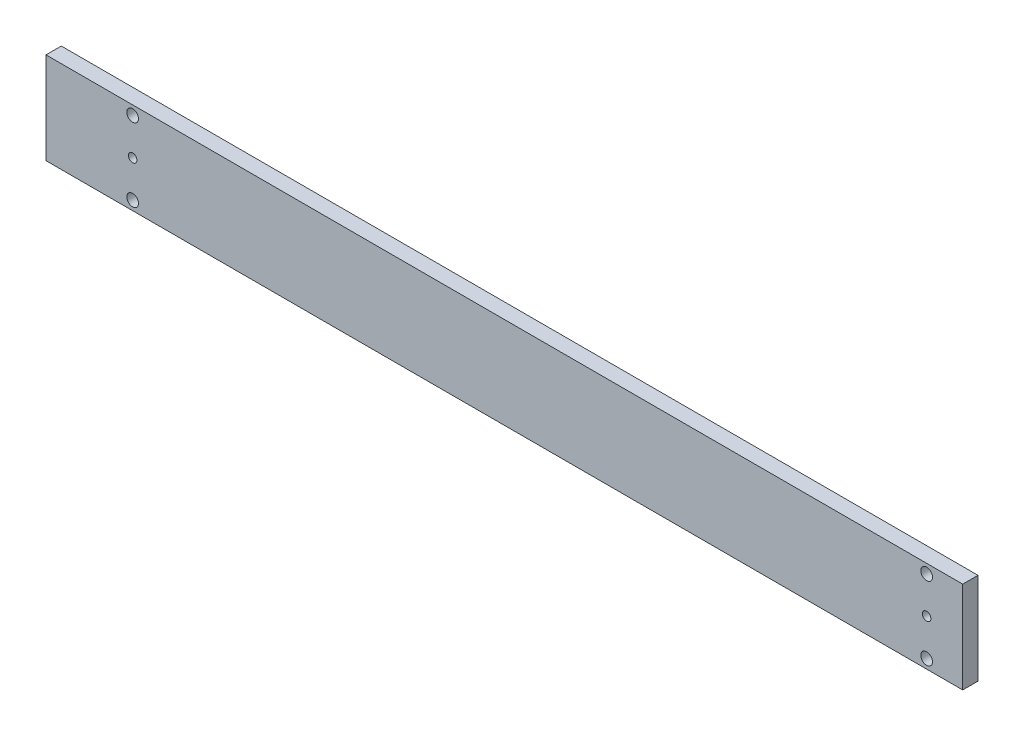
SolidWorks part; units mm, degrees
ref_plane "Front Plane" through (0, 0, 0) normal (0, 0, 1) x (1, 0, 0)
ref_plane "Top Plane" through (0, 0, 0) normal (0, 1, 0) x (1, 0, 0)
ref_plane "Right Plane" through (0, 0, 0) normal (1, 0, 0) x (0, 0, -1)
sketch "Sketch1" plane through (0, 0, 0) normal (0, 0, 1) x (1, 0, 0)
  line L0 (18, 17.145) -> (18, 1.905) construction
  line L1 (0, 0) -> (190.5, 0)
  line L2 (0, 0) -> (0, 19.05)
  line L3 (0, 19.05) -> (190.5, 19.05)
  line L4 (190.5, 0) -> (190.5, 19.05)
  line L5 (18, 9.525) -> (0, 9.525) construction
  line L6 (183, 17.145) -> (183, 1.905) construction
  line L7 (183, 9.525) -> (18, 9.525) construction
  circle A0 centre (18, 17.145) radius 1.2192
  circle A1 centre (18, 1.905) radius 1.2192
  circle A2 centre (183, 17.145) radius 1.2192
  circle A3 centre (183, 1.905) radius 1.2192
  circle A4 centre (183, 9.525) radius 0.889
  circle A5 centre (18, 9.525) radius 0.889
  dimension "D3" = 2.4384
  dimension "D7" = 15.24
  dimension "D8" = 1.778
  dimension "D1" = 190.5
  dimension "D2" = 19.05
  dimension "D4" = 7.5
  dimension "D5" = 15.24
  dimension "D6" = 165
extrude "Boss-Extrude1" add sketch "Sketch1" along normal blind 3.175
